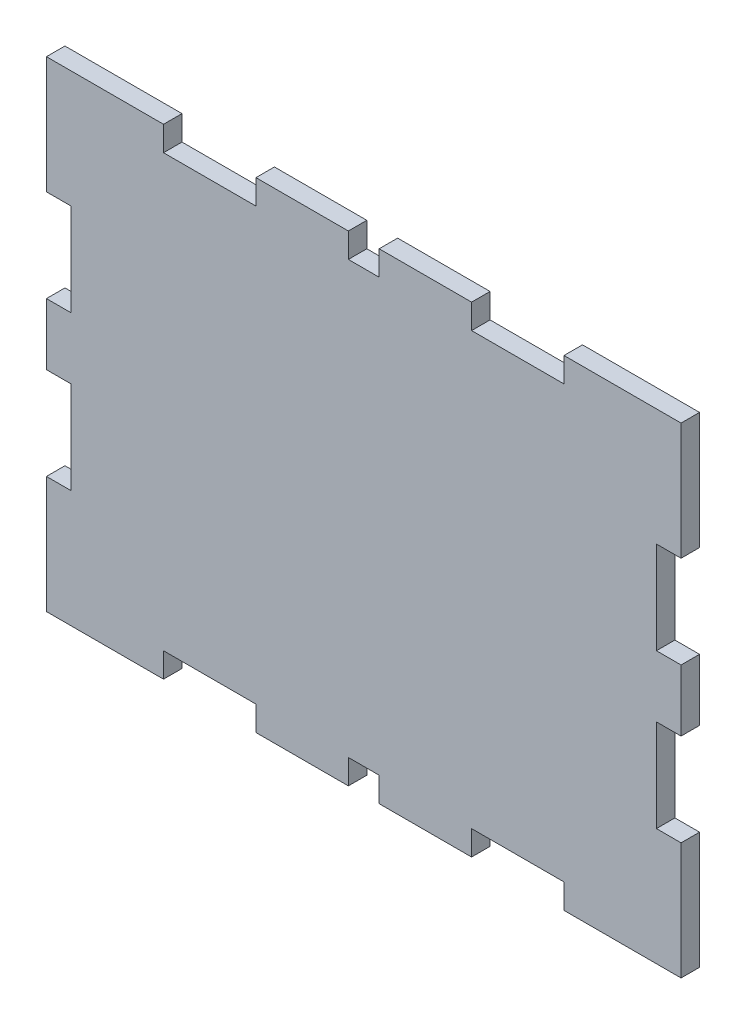
SolidWorks part; units mm, degrees
ref_plane "Front Plane" through (0, 0, 0) normal (0, 0, 1) x (1, 0, 0)
ref_plane "Top Plane" through (0, 0, 0) normal (0, 1, 0) x (1, 0, 0)
ref_plane "Right Plane" through (0, 0, 0) normal (1, 0, 0) x (0, 0, -1)
sketch "Sketch1" plane through (0, 0, 0) normal (0, 0, 1) x (1, 0, 0)
  line L1 (0, 0) -> (-95, 0)
  line L2 (0, 0) -> (0, 70)
  line L3 (0, 70) -> (-95, 70)
  line L4 (-95, 0) -> (-95, 70)
  dimension "D1" = 95
  dimension "D2" = 70
extrude "Boss-Extrude1" add sketch "Sketch1" along normal blind 3
sketch "Sketch2" plane through (0, 0, 3) normal (0, 0, 1) x (1, 0, 0)
  line L2 (0, 15) -> (4, 15)
  line L3 (0, 30) -> (4, 30)
  line L6 (-95, 70) -> (-80, 70)
  line L7 (-80, 74) -> (-80, 70)
  line L8 (4, -4) -> (4, 74)
  line L9 (4, 74) -> (-99, 74)
  line L10 (-99, 74) -> (-99, -4)
  line L11 (-99, -4) -> (4, -4)
  line L13 (0, 74) -> (-15, 74)
  line L16 (-65, 74) -> (-65, 70)
  line L17 (-15, 74) -> (-15, 70)
  line L18 (-30, 74) -> (-30, 70)
  line L19 (-50, 74) -> (-50, 70)
  line L20 (-45, 74) -> (-45, 70)
  line L21 (-50, 74) -> (-65, 74)
  line L22 (-45, 70) -> (-30, 70)
  line L23 (-80, 74) -> (-95, 74)
  line L24 (-65, 70) -> (-50, 70)
  line L25 (-30, 74) -> (-45, 74)
  line L26 (-15, 70) -> (0, 70)
  line L27 (-95, 35) -> (0, 35) construction
  line L28 (-95, 70) -> (-95, 0) construction
  line L29 (0, 0) -> (0, 70) construction
  line L30 (-15, 0) -> (0, 0)
  line L31 (-30, -4) -> (-45, -4)
  line L32 (-65, 0) -> (-50, 0)
  line L33 (-80, -4) -> (-95, -4)
  line L34 (-45, 0) -> (-30, 0)
  line L35 (-50, -4) -> (-65, -4)
  line L36 (-45, -4) -> (-45, 0)
  line L37 (-50, -4) -> (-50, 0)
  line L38 (-30, -4) -> (-30, 0)
  line L39 (-15, -4) -> (-15, 0)
  line L40 (-65, -4) -> (-65, 0)
  line L41 (0, -4) -> (-15, -4)
  line L42 (-80, -4) -> (-80, 0)
  line L43 (-95, 0) -> (-80, 0)
  line L46 (0, 55) -> (4, 55)
  line L47 (0, 40) -> (4, 40)
  line L48 (-47.5, 70) -> (-47.5, 0) construction
  line L49 (0, 70) -> (-95, 70) construction
  line L50 (-95, 0) -> (0, 0) construction
  line L51 (0, 70) -> (0, 55)
  line L53 (-95, 70) -> (-95, 55)
  line L54 (-99, 0) -> (-99, 15)
  line L56 (-95, 40) -> (-99, 40)
  line L57 (-95, 55) -> (-99, 55)
  line L58 (4, 0) -> (4, 70)
  line L59 (4, 0) -> (4, 15)
  line L60 (-95, 30) -> (-99, 30)
  line L61 (-95, 15) -> (-99, 15)
  line L62 (-99, 55) -> (-99, 70)
  line L63 (-95, 40) -> (-95, 30)
  line L64 (-99, 30) -> (-99, 40)
  line L65 (-95, 15) -> (-95, 0)
  line L66 (4, 55) -> (4, 70)
  line L67 (0, 40) -> (0, 30)
  line L68 (4, 30) -> (4, 40)
  line L69 (0, 15) -> (0, 0)
  line L70 (-95, 74) -> (-99, 74)
  line L71 (-99, 74) -> (-99, 70)
  line L72 (-99, 0) -> (-99, -4)
  line L73 (-99, -4) -> (-95, -4)
  line L74 (4, 0) -> (4, -4)
  line L75 (4, -4) -> (0, -4)
  line L76 (0, 74) -> (4, 74)
  line L77 (4, 74) -> (4, 70)
  dimension "D4" = 15
  dimension "D5" = 15
  dimension "D6" = 15
  dimension "D7" = 15
  dimension "D11" = 15
  dimension "D12" = 15
  dimension "D1" = 4
  dimension "D8" = 4
extrude "Boss-Extrude2" add sketch "Sketch2" against normal blind 3
